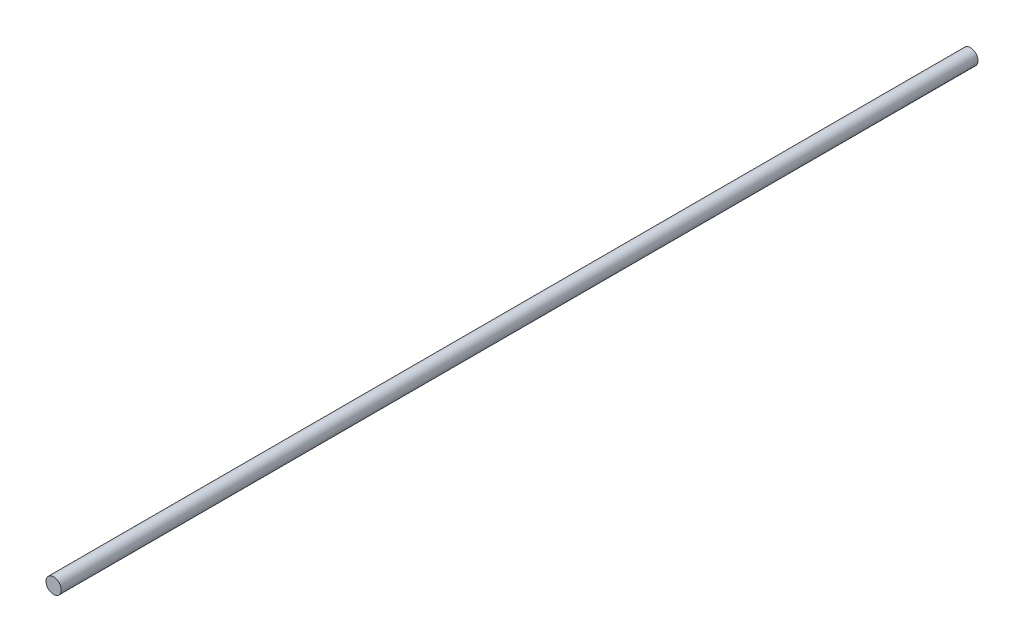
SolidWorks part; units mm, degrees
material "AISI 304"
ref_plane "前视基准面" through (0, 0, 0) normal (0, 0, 1) x (1, 0, 0)
ref_plane "上视基准面" through (0, 0, 0) normal (0, 1, 0) x (1, 0, 0)
ref_plane "右视基准面" through (0, 0, 0) normal (1, 0, 0) x (0, 0, -1)
sketch "草图1" plane through (0, 0, 0) normal (0, 0, 1) x (1, 0, 0)
  circle A0 centre (0, 0) radius 0.5
  dimension "D1" = 1
extrude "凸台-拉伸1" add sketch "草图1" along normal blind 60
